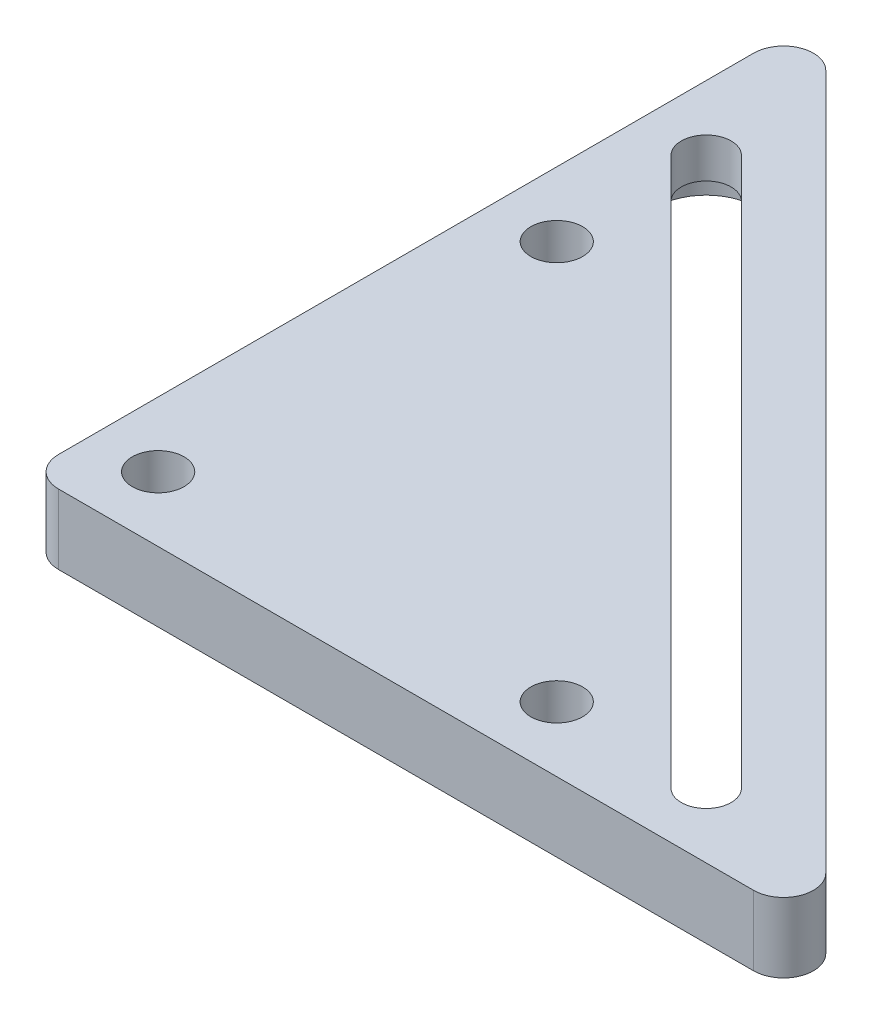
SolidWorks part; units mm, degrees
ref_plane "前视基准面" through (0, 0, 0) normal (0, 0, 1) x (1, 0, 0)
ref_plane "上视基准面" through (0, 0, 0) normal (0, 1, 0) x (1, 0, 0)
ref_plane "右视基准面" through (0, 0, 0) normal (1, 0, 0) x (0, 0, -1)
other "Configuration Table"
sketch "草图1" plane through (0, 0, 0) normal (0, 1, 0) x (1, 0, 0)
  line L0 (0, 0) -> (0, 80)
  line L1 (0, 0) -> (80, 0)
  line L2 (0, 80) -> (80, 0)
  dimension "D1" = 80
  dimension "D2" = 80
extrude "凸台-拉伸1" add sketch "草图1" along normal blind 10
sketch "草图2" plane through (0, 0, 0) normal (0, -1, 0) x (1, 0, 0)
  line L0 (6.5, -61.5) -> (61.5, -6.5)
  line L1 (2.9645, -57.9645) -> (57.9645, -2.9645)
  line L2 (10.0355, -65.0355) -> (65.0355, -10.0355)
  line L3 (80, 0) -> (0, -80)
  line L4 (0, 0) -> (80, 0)
  line L5 (0, -6.5) -> (80, -6.5)
  line L6 (0, 0) -> (0, -80)
  line L7 (6.5, 0) -> (6.5, -80)
  circle A0 centre (6.5, -6.5) radius 3
  circle A1 centre (61.5, -6.5) radius 5
  circle A2 centre (6.5, -61.5) radius 5
  dimension "D3" = 6
  dimension "D4" = 10
  dimension "D6" = 10
  dimension "D5" = 55
  dimension "D7" = 55
  dimension "D1" = 6.5
  dimension "D2" = 6.5
sketch "草图5" plane through (0, 10, 0) normal (0, 1, 0) x (1, 0, 0)
  line L0 (6.5, 0) -> (6.5, 80) construction
  line L1 (0, 6.5) -> (80, 6.5) construction
  circle A0 centre (6.5, 6.5) radius 2.6
  circle A1 centre (6.5, 46.5) radius 2.6
  circle A2 centre (46.5, 6.5) radius 2.6
  dimension "D2" = 5.2
  dimension "D3" = 5.2
  dimension "D4" = 5.2
  dimension "D1" = 40
  dimension "D5" = 40
extrude "切除-拉伸3" cut sketch "草图5" against normal blind 10
fillet "圆角5" radius 3 1 edges at (80, 5, 0)
fillet "圆角6" radius 3 1 edges at (0, 5, -80)
fillet "圆角7" radius 3 1 edges at (0, 5, 0)
sketch "草图7" plane through (0, 10, 0) normal (0, 1, 0) x (1, 0, 0)
  circle A0 centre (6.5, 6.5) radius 5.5
  circle A1 centre (6.5, 46.5) radius 5.5
  circle A2 centre (46.5, 6.5) radius 5.5
  dimension "D1" = 11
  dimension "D2" = 11
  dimension "D3" = 11
extrude "切除-拉伸4" cut sketch "草图7" against normal blind 5
sketch "草图10" plane through (0, 10, 0) normal (0, 1, 0) x (1, 0, 0)
  line L1 (-89.9322, -86.5453) -> (80.7675, -86.5453)
  line L2 (-89.9322, -86.5453) -> (-89.9322, 80.4467)
  line L3 (-89.9322, 80.4467) -> (80.7675, 80.4467)
  line L4 (80.7675, -86.5453) -> (80.7675, 80.4467)
  line L5 (-89.9322, -86.5453) -> (80.7675, 80.4467) construction
  line L6 (-89.9322, 80.4467) -> (80.7675, -86.5453) construction
  point P0 (-4.5824, -3.0493)
sketch "草图12" plane through (0, 0, 0) normal (0, -1, 0) x (1, 0, 0)
  line L0 (-993.5, -46.5) -> (49006.5, -46.5) construction
  circle A0 centre (8.5, -46.5) radius 2.5537
  circle A1 centre (6.5, -46.5) radius 2.6 construction
  dimension "D1" = 2
extrude "切除-拉伸9" cut sketch "草图12" against normal blind 9
sketch "草图13" plane through (0, 0, 0) normal (0, -1, 0) x (1, 0, 0)
  circle A0 centre (6.5, -46.5) radius 2.6
  circle A1 centre (8.5, -46.5) radius 2.5537
  arc M6 (7.5597, -48.8743) -> (7.5597, -44.1257) centre (6.5, -46.5) cw
extrude "凸台-拉伸2" add sketch "草图13" against normal blind 5 contours A1 M6
sketch "草图14" plane through (0, 5, 0) normal (0, 1, 0) x (1, 0, 0)
  circle A0 centre (6.5, 46.5) radius 5.5
  circle A1 centre (8.5, 46.5) radius 5.5
  circle M3 centre (6.5, 46.5) radius 5.5
  dimension "D1" = 11
extrude "切除-拉伸12" cut sketch "草图14" along normal blind 5 contours A1 M3
sketch "草图21" plane through (0, 5, 0) normal (0, 1, 0) x (1, 0, 0)
  circle A0 centre (8.5, 46.5) radius 5.5
  circle A1 centre (6.5, 46.5) radius 5.5
  arc M2 (7.5, 51.9083) -> (7.5, 41.0917) centre (6.5, 46.5) ccw
extrude "凸台-拉伸6" add sketch "草图21" along normal blind 5 contours A0 M2
sketch "草图22" plane through (0, 5, 0) normal (0, 1, 0) x (1, 0, 0)
  circle A0 centre (8.5, 46.5) radius 5.5
extrude "凸台-拉伸7" add sketch "草图22" along normal blind 5
sketch "草图24" plane through (0, 10, 0) normal (0, 1, 0) x (1, 0, 0)
  circle A0 centre (8.5, 46.5) radius 5.5
extrude "切除-拉伸14" cut sketch "草图24" against normal blind 3
sketch "草图25" plane through (0, 5, 0) normal (0, -1, 0) x (1, 0, 0)
  circle A0 centre (8.5, -46.5) radius 2.65
  dimension "D1" = 5.3
extrude "切除-拉伸15" cut sketch "草图25" against normal blind 3
sketch "草图26" plane through (0, 0, 0) normal (0, -1, 0) x (1, 0, 0)
  circle A0 centre (8.5, -46.5) radius 2.65
  dimension "D1" = 5.3
extrude "切除-拉伸16" cut sketch "草图26" against normal blind 5
sketch "草图29" plane through (0, 0, 0) normal (0, -1, 0) x (1, 0, 0)
  circle A0 centre (8.5, -46.5) radius 2.65
extrude "凸台-拉伸8" add sketch "草图29" against normal blind 10
sketch "草图30" plane through (0, 7, 0) normal (0, 1, 0) x (1, 0, 0)
  circle A0 centre (8.5, 46.5) radius 5.5
extrude "凸台-拉伸9" add sketch "草图30" along normal blind 3
extrude "切除-拉伸18" cut sketch "草图2" against normal blind 3 contours A2 L0 A1 L5 L1 L7 | A2 L2 A1 L0 | L7 A2 | L7 A2 L0 | L0 A2 L7 | A2 L7 L1 | A1 L1 L5 | L5 A1 | L5 A1 L0 | A1 L5 L0
sketch "草图33" plane through (0, 10, 0) normal (0, 1, 0) x (1, 0, 0)
  circle A0 centre (6.5, 6.5) radius 5.5
  circle A1 centre (6.5, 6.5) radius 2.6
  circle A2 centre (46.5, 6.5) radius 2.6
  circle A3 centre (46.5, 6.5) radius 5.5
extrude "凸台-拉伸10" add sketch "草图33" against normal blind 5
sketch "草图34" plane through (0, 10, 0) normal (0, 1, 0) x (1, 0, 0)
  line L1 (-21.8892, 87.5282) -> (96.7667, 87.5282)
  line L2 (-21.8892, 87.5282) -> (-21.8892, -20.9465)
  line L3 (-21.8892, -20.9465) -> (96.7667, -20.9465)
  line L4 (96.7667, 87.5282) -> (96.7667, -20.9465)
extrude "切除-拉伸20" cut sketch "草图34" against normal blind 3
sketch "草图35" plane through (0, 3, 0) normal (0, -1, 0) x (1, 0, 0)
  line L4 (8.2678, -63.2678) -> (63.2678, -8.2678)
  line L5 (59.7322, -4.7322) -> (4.7322, -59.7322)
  line L6 (8.2678, -63.2678) -> (63.2678, -8.2678)
  line L7 (59.7322, -4.7322) -> (4.7322, -59.7322)
  arc A4 (63.2678, -8.2678) -> (59.7322, -4.7322) centre (61.5, -6.5) ccw
  arc A5 (4.7322, -59.7322) -> (8.2678, -63.2678) centre (6.5, -61.5) ccw
  arc A6 (63.2678, -8.2678) -> (59.7322, -4.7322) centre (61.5, -6.5) ccw
  arc A7 (4.7322, -59.7322) -> (8.2678, -63.2678) centre (6.5, -61.5) ccw
  dimension "D1" = 2.5
extrude "切除-拉伸21" cut sketch "草图35" against normal through all
sketch "草图36" plane through (0, 7, 0) normal (0, 1, 0) x (1, 0, 0)
  line L1 (6.5, 6.5) -> (46.5, 6.5)
  line L2 (6.5, 6.5) -> (6.5, 46.5)
  circle A0 centre (6.5, 46.5) radius 2.6
  dimension "D2" = 5.2
  dimension "D1" = 40
extrude "切除-拉伸23" cut sketch "草图36" against normal through all
